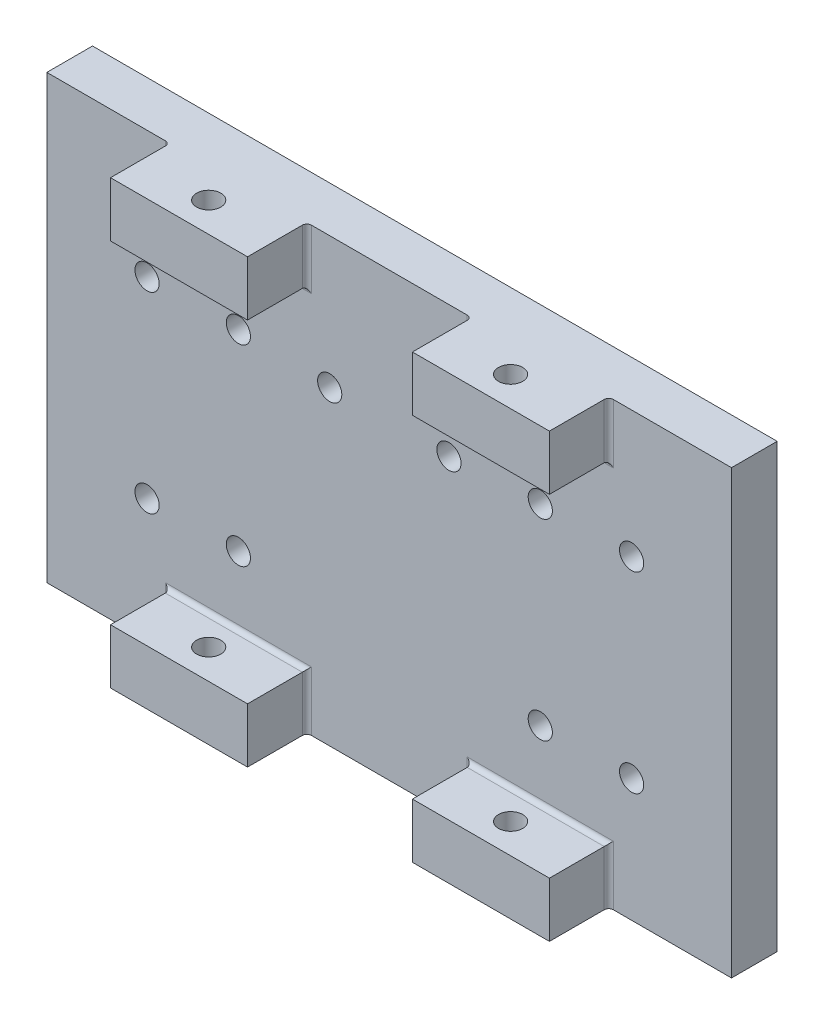
SolidWorks part; units mm, degrees
ref_plane "Front Plane" through (0, 0, 0) normal (0, 0, 1) x (1, 0, 0)
ref_plane "Top Plane" through (0, 0, 0) normal (0, 1, 0) x (1, 0, 0)
ref_plane "Right Plane" through (0, 0, 0) normal (1, 0, 0) x (0, 0, -1)
sketch "Sketch3" plane through (0, 0, 0) normal (0, 0, 1) x (1, 0, 0)
  line L52 (-75.0004, 52.83) -> (74.9996, 52.83)
  line L54 (74.9996, 52.83) -> (-75.0004, 52.83)
  line L57 (-75.0004, 52.83) -> (74.9287, 52.83)
  line L58 (-75.0004, 52.83) -> (-75.0004, -43.95)
  line L59 (-75.0004, -43.95) -> (74.9287, -43.95)
  line L60 (74.9287, 52.83) -> (74.9287, -43.95)
  line L65 (-43.2925, 25.0274) -> (-43.2925, 24.0274)
  line L67 (-53.0554, 24.0274) -> (-53.0554, 25.0274)
  line L68 (-33.055, 24.0274) -> (-33.055, 25.0274)
  line L70 (43.4815, 25.0274) -> (43.4815, 24.0274)
  circle A20 centre (-53.0554, -17.005) radius 2.65
  circle A32 centre (-33.055, -17.005) radius 2.65
  circle A35 centre (33.055, -17.005) radius 2.65
  circle A36 centre (53.0546, -17.005) radius 2.65
  circle A38 centre (-13.055, 24.0274) radius 2.65
  circle A39 centre (13.055, 24.0274) radius 2.65
  circle A48 centre (53.0546, 25.0274) radius 2.65
  circle A49 centre (-53.0554, 25.0274) radius 2.65
  circle A50 centre (-33.055, 25.0274) radius 2.65
  circle A51 centre (33.055, 25.0274) radius 2.65
  point P0 (0, 0)
  dimension "D3" = 5.3
  dimension "D4" = 96.78
  dimension "D6" = 5.3
  dimension "D7" = 1
  dimension "D8" = 5.3
  dimension "D13" = 5.3
  dimension "D11" = 5.3
  dimension "D18" = 5.3
  dimension "D5" = 5.3
  dimension "D22" = 5.3
  dimension "D24" = 5.3
  dimension "D25" = 5.3
  dimension "D10" = 1
extrude "Boss-Extrude1" add sketch "Sketch3" along normal blind 10
sketch "Sketch4" plane through (0, 0, 10) normal (0, 0, 1) x (1, 0, 0)
  line L0 (-75.0004, -43.95) -> (74.9287, -43.95) construction
  line L1 (-75.0004, 52.83) -> (74.9287, 52.83) construction
  line L2 (-33.055, 40.83) -> (-48.055, 40.83)
  line L3 (-48.055, -43.95) -> (-18.055, -43.95)
  line L4 (-48.055, -43.95) -> (-48.055, -31.95)
  line L5 (-48.055, 40.83) -> (-18.055, 40.83)
  line L6 (-48.055, 40.83) -> (-48.055, 52.83)
  line L7 (-48.055, 52.83) -> (-18.055, 52.83)
  line L8 (-18.055, 40.83) -> (-18.055, 52.83)
  line L9 (-48.055, -31.95) -> (-18.055, -31.95)
  line L10 (18.055, 40.83) -> (48.055, 40.83)
  line L11 (18.055, 40.83) -> (18.055, 52.83)
  line L12 (18.055, 52.83) -> (48.055, 52.83)
  line L13 (48.055, 40.83) -> (48.055, 52.83)
  line L14 (-18.055, -43.95) -> (-18.055, -31.95)
  line L16 (18.055, -43.95) -> (48.055, -43.95)
  line L17 (18.055, -43.95) -> (18.055, -31.95)
  line L18 (18.055, -31.95) -> (48.055, -31.95)
  line L19 (48.055, -43.95) -> (48.055, -31.95)
  line M12 (74.9287, 52.83) -> (-75.0004, 52.83)
  dimension "D1" = 30
  dimension "D2" = 12
  dimension "D3" = 12
  dimension "D4" = 12
  dimension "D5" = 30
  dimension "D6" = 12
extrude "Boss-Extrude4" add sketch "Sketch4" along normal blind 13 contours L5 L8 L6 L2 M12 | L10 L13 L11 M12 | L4 L3 L14 L9 | L17 L16 L19 L18
sketch "Sketch8" plane through (0, -31.95, 0) normal (0, 1, 0) x (1, 0, 0)
  circle A0 centre (-33.055, -16.5) radius 2.65
  circle A1 centre (33.055, -16.5) radius 2.65
  dimension "D1" = 5.3
  dimension "D3" = 5.3
extrude "Cut-Extrude1" cut sketch "Sketch8" along normal through all both and the other way through all
fillet "Fillet1" radius 1 12 edges at (48.055, -37.95, 10) (33.055, -31.95, 10) (18.055, -37.95, 10) (-18.055, -37.95, 10) (-33.055, -31.95, 10) (-48.055, -37.95, 10) (18.055, 46.83, 10) (33.055, 40.83, 10) (48.055, 46.83, 10) (-48.055, 46.83, 10) (-18.055, 46.83, 10) (-33.055, 40.83, 10)
